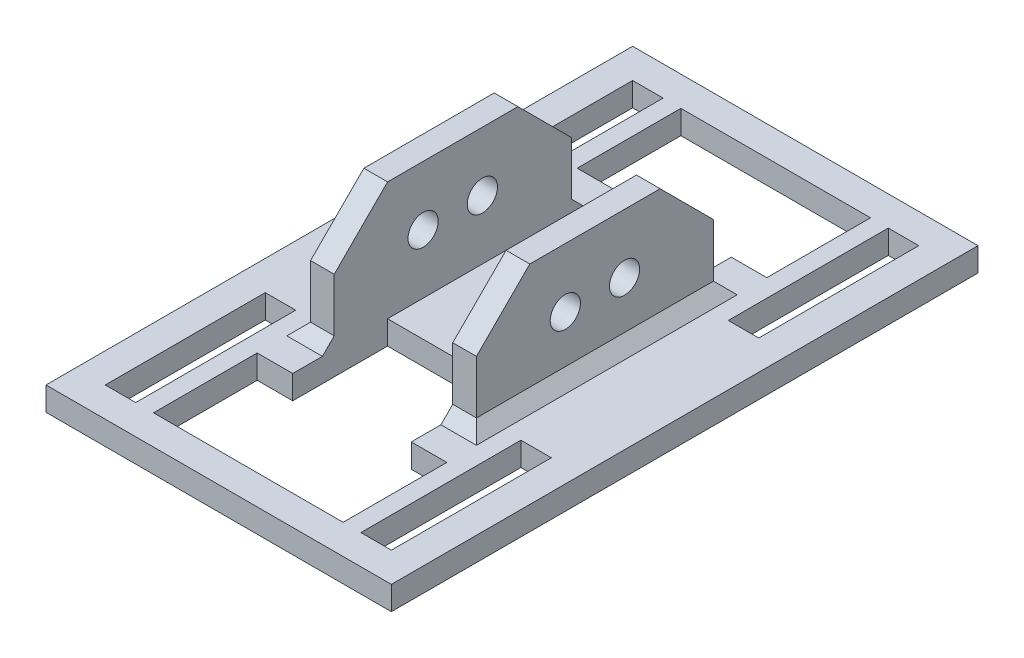
SolidWorks part; units mm, degrees
ref_plane "Front Plane" through (0, 0, 0) normal (0, 0, 1) x (1, 0, 0)
ref_plane "Top Plane" through (0, 0, 0) normal (0, 1, 0) x (1, 0, 0)
ref_plane "Right Plane" through (0, 0, 0) normal (1, 0, 0) x (0, 0, -1)
sketch "Sketch1" plane through (0, 0, 0) normal (0, 1, 0) x (1, 0, 0)
  line L0 (-5, 94) -> (-5, -5)
  line L1 (0, 89) -> (5.14, 89)
  line L2 (0, 89) -> (0, 62)
  line L3 (0, 62) -> (5.14, 62)
  line L4 (5.14, 89) -> (5.14, 62)
  line L5 (43.14, 89) -> (48.28, 89)
  line L6 (43.14, 89) -> (43.14, 62)
  line L7 (43.14, 62) -> (48.28, 62)
  line L8 (48.28, 89) -> (48.28, 62)
  line L9 (0, 27) -> (5.14, 27)
  line L10 (0, 27) -> (0, 0)
  line L11 (0, 0) -> (5.14, 0)
  line L12 (5.14, 27) -> (5.14, 0)
  line L13 (43.14, 27) -> (48.28, 27)
  line L14 (43.14, 27) -> (43.14, 0)
  line L15 (43.14, 0) -> (48.28, 0)
  line L16 (48.28, 27) -> (48.28, 0)
  line L21 (-5, -5) -> (53.28, -5)
  line L22 (53.28, 94) -> (53.28, -5)
  line L23 (-5, 94) -> (53.28, 94)
  dimension "D1" = 89
  dimension "D2" = 5.14
  dimension "D3" = 27
  dimension "D4" = 38
  dimension "D5" = 5
  dimension "D6" = 5
  dimension "D7" = 5
  dimension "D8" = 5
extrude "Boss-Extrude1" add sketch "Sketch1" along normal blind 4
sketch "Sketch2" plane through (0, 4, 0) normal (0, 1, 0) x (1, 0, 0)
  line L0 (24.14, 94) -> (24.14, -5) construction
  line L1 (53.28, 94) -> (-5, 94) construction
  line L2 (-5, -5) -> (53.28, -5) construction
  line L3 (-5, 44.5) -> (53.28, 44.5) construction
  line L4 (14.14, 64.5) -> (34.14, 64.5) construction
  line L5 (14.14, 64.5) -> (14.14, 24.5) construction
  line L6 (14.14, 24.5) -> (34.14, 24.5) construction
  line L7 (34.14, 64.5) -> (34.14, 24.5) construction
  line L8 (-5, 94) -> (-5, -5) construction
  line L9 (53.28, -5) -> (53.28, 94) construction
  line L11 (14.14, 64.5) -> (10.14, 64.5)
  line L12 (14.14, 64.5) -> (14.14, 24.5)
  line L13 (14.14, 24.5) -> (10.14, 24.5)
  line L14 (10.14, 64.5) -> (10.14, 24.5)
  line L15 (34.14, 64.5) -> (38.14, 64.5)
  line L16 (34.14, 64.5) -> (34.14, 24.5)
  line L17 (34.14, 24.5) -> (38.14, 24.5)
  line L18 (38.14, 64.5) -> (38.14, 24.5)
  dimension "D1" = 20
  dimension "D2" = 40
  dimension "D3" = 20
  dimension "D4" = 4
extrude "Boss-Extrude2" add sketch "Sketch2" along normal blind 20
sketch "Sketch3" plane through (38.14, 0, 0) normal (1, 0, 0) x (0, 0, -1)
  line L0 (24.5, 14) -> (64.5, 14) construction
  line L1 (24.5, 24) -> (24.5, 4) construction
  line L2 (64.5, 24) -> (64.5, 4) construction
  circle A0 centre (39.5, 14) radius 2.55
  circle A1 centre (49.5, 14) radius 2.55
  dimension "D1" = 5.1
  dimension "D2" = 10
  dimension "D3" = 15
extrude "Cut-Extrude1" cut sketch "Sketch3" against normal up to surface (28 mm away) up to face at (10.14, 14, -44.5)
chamfer "Chamfer1" distance 2 angle 45 6 edges at (12.14, 4, -64.5) (10.14, 4, -44.5) (12.14, 4, -24.5) (36.14, 4, -64.5) (36.14, 4, -24.5) (38.14, 4, -44.5)
sketch "Sketch4" plane through (10.14, 0, 0) normal (-1, 0, 0) x (0, 0, 1)
  line L0 (-55.5, 24) -> (-64.5, 15)
  line L1 (-64.5, 24) -> (-24.5, 24) construction
  line L2 (-64.5, 24) -> (-64.5, 6) construction
  line L3 (-64.5, 15) -> (-64.5, 24)
  line L4 (-64.5, 24) -> (-55.5, 24)
  line L5 (-33.5, 24) -> (-24.5, 15)
  line L6 (-24.5, 24) -> (-24.5, 6) construction
  line L7 (-24.5, 15) -> (-24.5, 24)
  line L8 (-24.5, 24) -> (-33.5, 24)
  dimension "D1" = 45
extrude "Cut-Extrude2" cut sketch "Sketch4" against normal up to surface (28 mm away) up to face at (38.14, 14, -42.05)
sketch "Sketch5" plane through (0, 4, 0) normal (0, 1, 0) x (1, 0, 0)
  line L0 (8.14, 66.5) -> (14.14, 66.5) construction
  line L1 (34.14, 66.5) -> (40.14, 66.5) construction
  line L2 (40.14, 22.5) -> (34.14, 22.5) construction
  line L3 (14.14, 22.5) -> (8.14, 22.5) construction
  line L4 (34.14, 66.5) -> (34.14, 22.5) construction
  line L5 (14.14, 22.5) -> (14.14, 66.5) construction
  line L6 (8.14, 66.5) -> (14.14, 66.5)
  line L7 (34.14, 66.5) -> (40.14, 66.5)
  line L8 (40.14, 22.5) -> (34.14, 22.5)
  line L9 (14.14, 22.5) -> (8.14, 22.5)
  line L10 (34.14, 66.5) -> (34.14, 55.5)
  line L11 (14.14, 22.5) -> (14.14, 33.5)
  line L12 (5.14, 89) -> (0, 89) construction
  line L13 (8.14, 89) -> (40.14, 89)
  line L14 (14.14, 71.5) -> (14.14, 55.5)
  line L15 (8.14, 0) -> (40.14, 0)
  line L16 (34.14, 71.5) -> (34.14, 55.5)
  line L17 (0, 0) -> (5.14, 0) construction
  line L18 (40.14, 66.5) -> (40.14, 22.5) construction
  line L21 (14.14, 17.5) -> (8.14, 17.5)
  line L22 (8.14, 0) -> (8.14, 17.5)
  line L25 (34.14, 17.5) -> (40.14, 17.5)
  line L26 (40.14, 0) -> (40.14, 17.5)
  line L29 (14.14, 71.5) -> (8.14, 71.5)
  line L30 (8.14, 89) -> (8.14, 71.5)
  line L33 (34.14, 71.5) -> (40.14, 71.5)
  line L34 (40.14, 89) -> (40.14, 71.5)
  line L35 (8.14, 22.5) -> (8.14, 66.5) construction
  line L36 (14.14, 55.5) -> (34.14, 55.5)
  line L37 (14.14, 33.5) -> (34.14, 33.5)
  line L38 (14.14, 55.5) -> (14.14, 66.5)
  line L39 (34.14, 33.5) -> (34.14, 22.5)
  line L40 (34.14, 33.5) -> (34.14, 17.5)
  line L41 (14.14, 33.5) -> (14.14, 17.5)
  line M24 (14.14, 66.5) -> (14.14, 22.5)
  line M48 (34.14, 22.5) -> (34.14, 66.5)
  dimension "D1" = 5
  dimension "D2" = 5
extrude "Cut-Extrude3" cut sketch "Sketch5" along direction (0, -1, 0) on the side against the normal up to surface (4 mm away) contours L34 L13 L30 L29 L14 L21 L22 L15 L26 L25 L16 L33 M24 M48 | L41 L21 L22 L15 L26 L25 L40 L37 M24 M48
